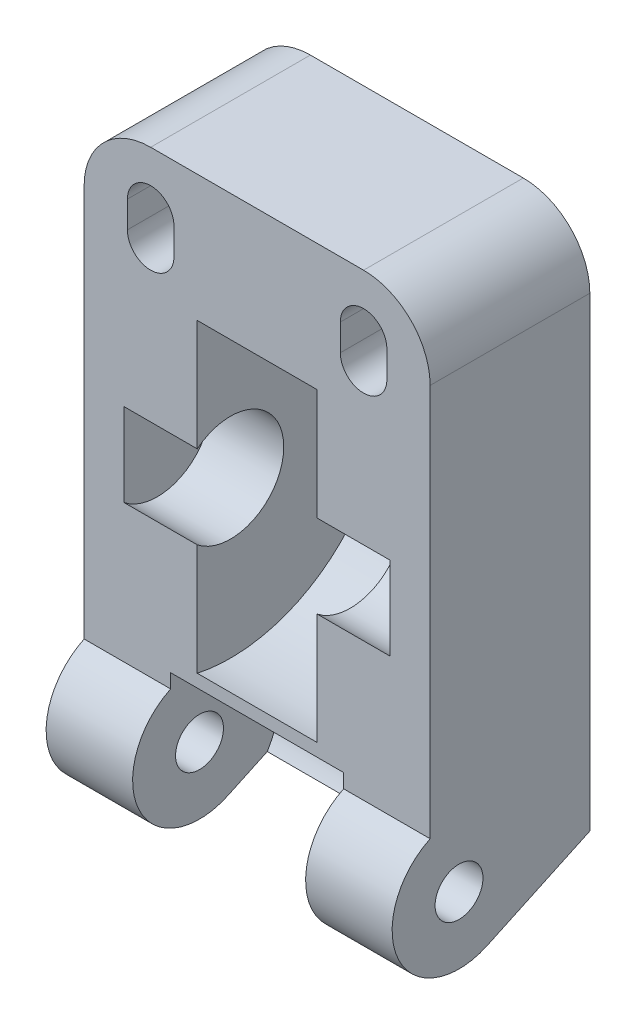
SolidWorks part; units mm, degrees
ref_plane "Front Plane" through (0, 0, 0) normal (0, 0, 1) x (1, 0, 0)
ref_plane "Top Plane" through (0, 0, 0) normal (0, 1, 0) x (1, 0, 0)
ref_plane "Right Plane" through (0, 0, 0) normal (1, 0, 0) x (0, 0, -1)
sketch "Sketch1" plane through (0, 0, 0) normal (1, 0, 0) x (0, 0, -1)
  line L0 (0, 0) -> (0, 40)
  line L1 (0, 0) -> (-7.7036, -3.5923)
  line L2 (0, 40) -> (-12, 40)
  line L5 (-12, 40) -> (-12, 5.5)
  arc A0 (-12, 5.5) -> (-7.7036, -3.5923) centre (-9.8286, 0.9648) ccw
  circle A1 centre (-9.8286, 0.9648) radius 1.8
  dimension "D8" = 3.6
  dimension "D1" = 8.5
  dimension "D2" = 40
  dimension "D3" = 115
  dimension "D4" = 34.5
  dimension "D5" = 12
extrude "Boss-Extrude1" add sketch "Sketch1" along normal mid plane 26
sketch "Sketch2" plane through (0, 0, 0) normal (1, 0, 0) x (0, 0, -1)
  line L0 (0, 19) -> (-9.5, 19) construction
  line L1 (0, 0) -> (0, 40) construction
  circle A0 centre (-9.5, 19) radius 4
  dimension "D2" = 8
  dimension "D1" = 9.5
  dimension "D3" = 19
extrude "Cut-Extrude1" cut sketch "Sketch2" against normal mid plane 20
sketch "Sketch3" plane through (0, 0, 0) normal (1, 0, 0) x (0, 0, -1)
  circle A0 centre (-9.5, 19) radius 11.75
  dimension "D1" = 23.5
extrude "Cut-Extrude2" cut sketch "Sketch3" against normal mid plane 9
sketch "Sketch4" plane through (0, 0, 0) normal (1, 0, 0) x (0, 0, -1)
  circle A0 centre (-9.8286, 0.9648) radius 6
  dimension "D1" = 12
extrude "Cut-Extrude3" cut sketch "Sketch4" against normal mid plane 13
sketch "Sketch7" plane through (0, 0, 0) normal (0, 0, -1) x (-1, 0, 0)
  line L0 (-8, 35.75) -> (-8, 33.75) construction
  line L1 (-6.25, 35.75) -> (-6.25, 33.75)
  line L2 (-9.75, 35.75) -> (-9.75, 33.75)
  line L3 (8, 35.75) -> (8, 33.75) construction
  line L4 (9.75, 35.75) -> (9.75, 33.75)
  line L5 (6.25, 35.75) -> (6.25, 33.75)
  line L6 (6.25, 34.75) -> (-6.25, 34.75) construction
  line L7 (0, 34.75) -> (0, 40) construction
  line L9 (-13, 40) -> (13, 40) construction
  line L10 (-13, 32) -> (13, 32) construction
  line L11 (-13, 0) -> (-13, 40) construction
  line L12 (13, 0) -> (13, 40) construction
  arc A0 (-6.25, 35.75) -> (-9.75, 35.75) centre (-8, 35.75) ccw
  arc A1 (-9.75, 33.75) -> (-6.25, 33.75) centre (-8, 33.75) ccw
  arc A2 (9.75, 35.75) -> (6.25, 35.75) centre (8, 35.75) ccw
  arc A3 (6.25, 33.75) -> (9.75, 33.75) centre (8, 33.75) ccw
  point P2 (-8, 34.75)
  point P7 (8, 34.75)
  point P16 (0, 40)
  dimension "D4" = 1.75
  dimension "D1" = 12.5
  dimension "D2" = 2
  dimension "D6" = 8
extrude "Cut-Extrude6" cut sketch "Sketch7" against normal through all
fillet "Fillet1" radius 5 2 edges at (-13, 40, 6) (13, 40, 6)
